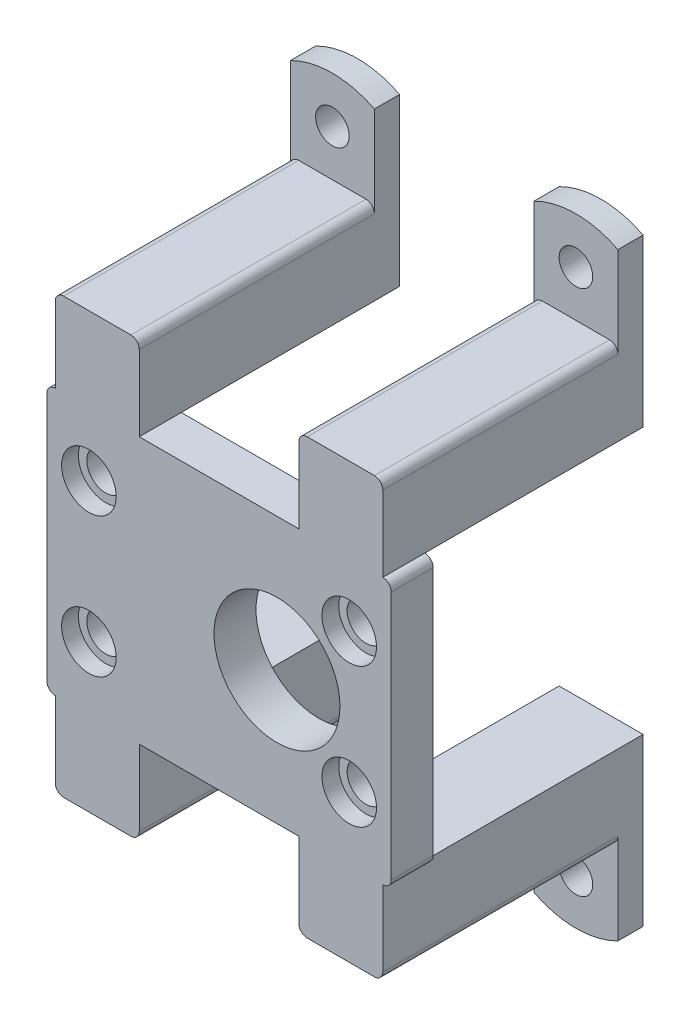
SolidWorks part; units mm, degrees
ref_plane "Front Plane" through (0, 0, 0) normal (0, 0, 1) x (1, 0, 0)
ref_plane "Top Plane" through (0, 0, 0) normal (0, 1, 0) x (1, 0, 0)
ref_plane "Right Plane" through (0, 0, 0) normal (1, 0, 0) x (0, 0, -1)
sketch "Sketch1" plane through (0, 0, 0) normal (0, 0, 1) x (1, 0, 0)
  line L0 (19.5, 25.85) -> (-19.5, 25.85)
  line L3 (-19.5, -25.85) -> (19.5, -25.85)
  line L5 (-19.5, -15.85) -> (19.5, -15.85)
  line L6 (20.5, -14.85) -> (20.5, 14.85)
  line L7 (19.5, 15.85) -> (-19.5, 15.85)
  line L8 (-20.5, 14.85) -> (-20.5, -1.4571)
  line L9 (-20.5, -1.4571) -> (-20.5, -14.85)
  line L10 (-19.5, -15.85) -> (19.5, -15.85)
  line L11 (20.5, -14.85) -> (20.5, 14.85)
  line L12 (19.5, 15.85) -> (-19.5, 15.85)
  line L13 (-20.5, 14.85) -> (-20.5, -1.4571)
  line L14 (-20.5, -1.4571) -> (-20.5, -14.85)
  line L15 (19.5, 15.85) -> (19.5, 25.85)
  line L16 (9.5, 25.85) -> (9.5, 15.85)
  line L17 (9.5, 15.85) -> (19.5, 15.85)
  line L18 (0, 0) -> (0, 39.3573) construction
  line L19 (-19.5, 15.85) -> (-19.5, 25.85)
  line L20 (-9.5, 25.85) -> (-9.5, 15.85)
  line L21 (19.5, -15.85) -> (19.5, -25.85)
  line L22 (30.5, -14.85) -> (30.5, 14.85) construction
  line L23 (-30.5, -1.4571) -> (-30.5, -14.85) construction
  line L24 (-30.5, 14.85) -> (-30.5, -1.4571) construction
  line L25 (-19.5, -25.85) -> (-19.5, -15.85)
  line L26 (-9.5, -15.85) -> (-9.5, -25.85)
  line L27 (9.5, -15.85) -> (9.5, -25.85)
  circle A0 centre (15.5, -8.3) radius 1.25 construction
  circle A1 centre (-15.5, -8.3) radius 1.25 construction
  circle A2 centre (-15.5, 8.3) radius 1.25 construction
  circle A3 centre (15.5, 8.3) radius 1.25 construction
  circle A4 centre (15.5, -8.3) radius 1.25
  circle A5 centre (-15.5, -8.3) radius 1.25
  circle A6 centre (-15.5, 8.3) radius 1.25
  circle A7 centre (15.5, 8.3) radius 1.25
  circle A8 centre (6.9, 0) radius 7.5 construction
  circle A9 centre (6.9, 0) radius 7.5
  circle A10 centre (15.5, 8.3) radius 2.25
  circle A11 centre (15.5, -8.3) radius 2.25
  circle A12 centre (-15.5, -8.3) radius 2.25
  circle A13 centre (-15.5, 8.3) radius 2.25
  arc A14 (19.5, -15.85) -> (20.5, -14.85) centre (19.5, -14.85) ccw
  arc A15 (20.5, 14.85) -> (19.5, 15.85) centre (19.5, 14.85) ccw
  arc A16 (-19.5, 15.85) -> (-20.5, 14.85) centre (-19.5, 14.85) ccw
  arc A17 (-20.5, -14.85) -> (-19.5, -15.85) centre (-19.5, -14.85) ccw
  arc A18 (19.5, -15.85) -> (20.5, -14.85) centre (19.5, -14.85) ccw
  arc A19 (20.5, 14.85) -> (19.5, 15.85) centre (19.5, 14.85) ccw
  arc A20 (-19.5, 15.85) -> (-20.5, 14.85) centre (-19.5, 14.85) ccw
  arc A21 (-20.5, -14.85) -> (-19.5, -15.85) centre (-19.5, -14.85) ccw
  arc A26 (19.5, -25.85) -> (30.5, -14.85) centre (19.5, -14.85) ccw construction
  arc A27 (30.5, 14.85) -> (19.5, 25.85) centre (19.5, 14.85) ccw construction
  arc A28 (-30.5, -14.85) -> (-19.5, -25.85) centre (-19.5, -14.85) ccw construction
  arc A29 (-19.5, 25.85) -> (-30.5, 14.85) centre (-19.5, 14.85) ccw construction
  dimension "D3" = 10
  dimension "D4" = 10
  dimension "D5" = 10
  dimension "D1" = 0
  dimension "D2" = 1
extrude "Boss-Extrude1" add sketch "Sketch1" along normal blind 5 contours L20 L0 L19 L12 | L0 L16 L12 L15 | L14 A21 L10 A18 L11 A19 L12 A20 L13 A9 A10 A11 A12 A13 | L10 L27 L3 L21 | L26 L10 L25 L3
sketch "Sketch2" plane through (0, 0, 0) normal (0, 0, -1) x (-1, 0, 0)
  line L0 (-19.5, -15.85) -> (-19.5, -25.85) construction
  line L1 (-19.5, -15.85) -> (-19.5, -25.85)
  line L2 (-9.5, -15.85) -> (-9.5, -25.85) construction
  line L3 (-9.5, -15.85) -> (-9.5, -25.85)
  line L4 (-9.5, -25.85) -> (-19.5, -25.85) construction
  line L5 (-9.5, -25.85) -> (-19.5, -25.85)
  line L6 (-19.5, -15.85) -> (-9.5, -15.85)
  line L7 (9.5, -15.85) -> (19.5, -15.85)
  line L8 (-19.5, 15.85) -> (-9.5, 15.85)
  line L9 (9.5, 15.85) -> (19.5, 15.85)
  line L23 (9.5, 25.85) -> (9.5, 15.85)
  line L24 (9.5, 15.85) -> (-9.5, 15.85)
  line L25 (-9.5, 15.85) -> (-9.5, 25.85)
  line L26 (-9.5, 25.85) -> (-19.5, 25.85)
  line L27 (-19.5, 25.85) -> (-19.5, 15.85)
  line L28 (-20.5, 14.85) -> (-20.5, -14.85)
  line L29 (-19.5, -15.85) -> (-19.5, -25.85)
  line L30 (-19.5, -25.85) -> (-9.5, -25.85)
  line L31 (-9.5, -25.85) -> (-9.5, -15.85)
  line L32 (-9.5, -15.85) -> (9.5, -15.85)
  line L33 (9.5, -15.85) -> (9.5, -25.85)
  line L34 (9.5, -25.85) -> (19.5, -25.85)
  line L35 (19.5, -25.85) -> (19.5, -15.85)
  line L36 (20.5, -14.85) -> (20.5, 14.85)
  line L37 (19.5, 15.85) -> (19.5, 25.85)
  line L38 (19.5, 25.85) -> (9.5, 25.85)
  line L39 (9.5, 25.85) -> (9.5, 15.85)
  line L40 (9.5, 15.85) -> (-9.5, 15.85)
  line L41 (-9.5, 15.85) -> (-9.5, 25.85)
  line L42 (-9.5, 25.85) -> (-19.5, 25.85)
  line L43 (-19.5, 25.85) -> (-19.5, 15.85)
  line L44 (-20.5, 14.85) -> (-20.5, -14.85)
  line L45 (-19.5, -15.85) -> (-19.5, -25.85)
  line L46 (-19.5, -25.85) -> (-9.5, -25.85)
  line L47 (-9.5, -25.85) -> (-9.5, -15.85)
  line L48 (-9.5, -15.85) -> (9.5, -15.85)
  line L49 (9.5, -15.85) -> (9.5, -25.85)
  line L50 (9.5, -25.85) -> (19.5, -25.85)
  line L51 (19.5, -25.85) -> (19.5, -15.85)
  line L52 (20.5, -14.85) -> (20.5, 14.85)
  line L53 (19.5, 15.85) -> (19.5, 25.85)
  line L54 (19.5, 25.85) -> (9.5, 25.85)
  arc A4 (-19.5, 15.85) -> (-20.5, 14.85) centre (-19.5, 14.85) ccw
  arc A5 (-20.5, -14.85) -> (-19.5, -15.85) centre (-19.5, -14.85) ccw
  arc A6 (19.5, -15.85) -> (20.5, -14.85) centre (19.5, -14.85) ccw
  arc A7 (20.5, 14.85) -> (19.5, 15.85) centre (19.5, 14.85) ccw
  arc A8 (-19.5, 15.85) -> (-20.5, 14.85) centre (-19.5, 14.85) ccw
  arc A9 (-20.5, -14.85) -> (-19.5, -15.85) centre (-19.5, -14.85) ccw
  arc A10 (19.5, -15.85) -> (20.5, -14.85) centre (19.5, -14.85) ccw
  arc A11 (20.5, 14.85) -> (19.5, 15.85) centre (19.5, 14.85) ccw
  line M21 (9.5, 25.85) -> (9.5, 15.85)
  line M23 (-9.5, 15.85) -> (-9.5, 25.85)
  line M24 (-9.5, 25.85) -> (-19.5, 25.85)
  line M25 (-19.5, 25.85) -> (-19.5, 15.85)
  line M29 (-19.5, -15.85) -> (-19.5, -25.85)
  line M30 (-19.5, -25.85) -> (-9.5, -25.85)
  line M31 (-9.5, -25.85) -> (-9.5, -15.85)
  line M33 (9.5, -15.85) -> (9.5, -25.85)
  line M34 (9.5, -25.85) -> (19.5, -25.85)
  line M35 (19.5, -25.85) -> (19.5, -15.85)
  line M39 (19.5, 15.85) -> (19.5, 25.85)
  line M40 (19.5, 25.85) -> (9.5, 25.85)
  dimension "D1" = 0
extrude "Boss-Extrude2" add sketch "Sketch2" along normal blind 26 contours L7 M33 M34 M35 | L6 M29 M30 M31 | L9 M21 M39 M40 | L8 M25 M23 M24
sketch "Sketch3" plane through (19.5, 0, 0) normal (1, 0, 0) x (0, 0, -1)
  line L0 (26, 15.85) -> (26, -15.85)
sketch "Sketch4" plane through (0, 0, -26) normal (0, 0, -1) x (-1, 0, 0)
  line L0 (9.5, -25.85) -> (19.5, -25.85) construction
  line L1 (14.5, -25.85) -> (14.5, -36.85) construction
  line L2 (9.5, -25.85) -> (9.5, -35.648)
  line L3 (19.5, -25.85) -> (19.5, -35.648)
  line L4 (0, 0) -> (0, -42.652) construction
  line L5 (0, 0) -> (-45.7719, 0) construction
  line L6 (-19.5, -25.85) -> (-19.5, -35.648)
  line L7 (-9.5, -25.85) -> (-9.5, -35.648)
  line L8 (19.5, -25.85) -> (9.5, -25.85)
  line L9 (-19.5, -25.85) -> (-9.5, -25.85)
  line L10 (19.5, 25.85) -> (19.5, 35.648)
  line L11 (19.5, 25.85) -> (9.5, 25.85)
  line L12 (9.5, 25.85) -> (9.5, 35.648)
  line L13 (-9.5, 25.85) -> (-9.5, 35.648)
  line L14 (-19.5, 25.85) -> (-19.5, 35.648)
  line L15 (-19.5, 25.85) -> (-9.5, 25.85)
  arc A0 (9.5, -35.648) -> (19.5, -35.648) centre (14.5, -25.85) ccw
  circle A2 centre (14.5, -31.35) radius 2
  arc A3 (-9.5, -35.648) -> (-19.5, -35.648) centre (-14.5, -25.85) cw
  circle A4 centre (-14.5, -31.35) radius 2
  arc A5 (9.5, 35.648) -> (19.5, 35.648) centre (14.5, 25.85) cw
  circle A6 centre (14.5, 31.35) radius 2
  arc A7 (-9.5, 35.648) -> (-19.5, 35.648) centre (-14.5, 25.85) ccw
  circle A8 centre (-14.5, 31.35) radius 2
  dimension "D1" = 22
  dimension "D2" = 4
extrude "Boss-Extrude3" add sketch "Sketch4" against normal blind 3
fillet "Fillet1" radius 1 8 edges at (9.5, 25.85, -9) (19.5, 25.85, -9) (19.5, -25.85, -9) (9.5, -25.85, -9) (-9.5, -25.85, -9) (-19.5, -25.85, -9) (-19.5, 25.85, -9) (-9.5, 25.85, -9)
sketch "Sketch5" plane through (0, 0, 5) normal (0, 0, 1) x (1, 0, 0)
  line L0 (0, 0) -> (30.0126, 0) construction
  circle A0 centre (-15.5, -8.3) radius 3.25
  circle A1 centre (-15.5, 8.3) radius 3.25
  circle A2 centre (15.5, -8.3) radius 3.25
  circle A3 centre (15.5, 8.3) radius 3.25
  dimension "D1" = 6.5
  dimension "D2" = 6.5
extrude "Cut-Extrude1" cut sketch "Sketch5" against normal blind 2
